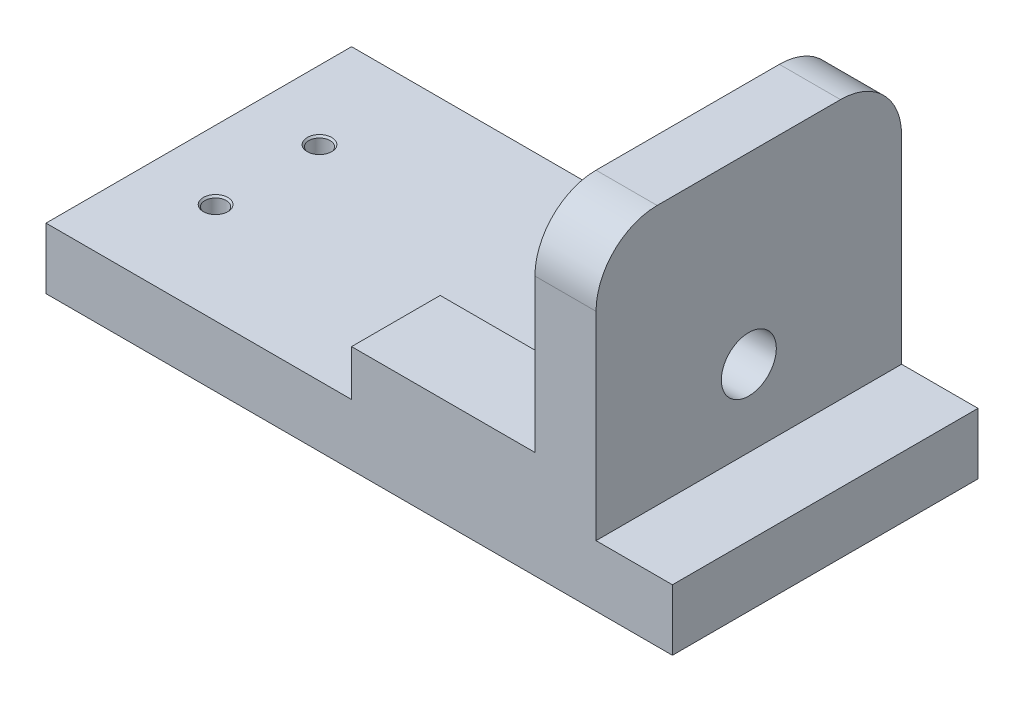
SolidWorks part; units mm, degrees
ref_plane "Piano frontale" through (0, 0, 0) normal (0, 0, 1) x (1, 0, 0)
ref_plane "Piano superiore" through (0, 0, 0) normal (0, 1, 0) x (1, 0, 0)
ref_plane "Piano destro" through (0, 0, 0) normal (1, 0, 0) x (0, 0, -1)
sketch "Schizzo1" plane through (0, 0, 0) normal (0, 1, 0) x (1, 0, 0)
  line L1 (-102.5, -50) -> (102.5, -50)
  line L2 (-102.5, -50) -> (-102.5, 50)
  line L3 (-102.5, 50) -> (102.5, 50)
  line L4 (102.5, -50) -> (102.5, 50)
  line L5 (-102.5, -50) -> (102.5, 50) construction
  line L6 (-102.5, 50) -> (102.5, -50) construction
  point P0 (0, 0)
  dimension "D1" = 100
  dimension "D2" = 205
extrude "Estrusione-Estrusione1" add sketch "Schizzo1" along normal blind 20
sketch "Schizzo2" plane through (0, 0, 0) normal (0, 1, 0) x (1, 0, 0)
  line L0 (77.5, 50) -> (77.5, -50)
  line L1 (102.5, 50) -> (-102.5, 50) construction
  line L2 (-102.5, -50) -> (102.5, -50) construction
  line L3 (77.5, -50) -> (-2.5, -50)
  line L4 (-2.5, -50) -> (-2.5, -21)
  line L5 (-2.5, -21) -> (57.5, -21)
  line L6 (57.5, -21) -> (57.5, 21)
  line L7 (57.5, 21) -> (-2.5, 21)
  line L8 (-2.5, 21) -> (-2.5, 50)
  line L9 (-2.5, 50) -> (77.5, 50)
  line L10 (102.5, -50) -> (102.5, 50) construction
  dimension "D1" = 20
  dimension "D2" = 80
  dimension "D3" = 25
  dimension "D4" = 29
extrude "Estrusione-Estrusione2" add sketch "Schizzo2" along normal blind 85 from surface at 20 starting at face at (0, 20, 0)
sketch "Schizzo4" plane through (0, 0, 0) normal (0, 0, 1) x (1, 0, 0)
  line L0 (-102.5, 20) -> (-2.5, 20) construction
  line L1 (-2.5, 105) -> (57.5, 105)
  line L2 (-2.5, 105) -> (-2.5, 35)
  line L3 (-2.5, 35) -> (57.5, 35)
  line L4 (57.5, 105) -> (57.5, 35)
  dimension "D1" = 20
  dimension "D2" = 15
extrude "Taglio-Estrusione1" cut sketch "Schizzo4" against normal through all both and the other way through all
sketch "Schizzo6" plane through (0, 0, 0) normal (1, 0, 0) x (0, 0, -1)
  line L0 (-50, 0) -> (50, 0) construction
  line L1 (-50, 105) -> (50, 105) construction
  line L2 (-50, 85) -> (-50, 105)
  line L3 (-50, 105) -> (-30, 105)
  line L4 (30, 105) -> (50, 105)
  line L5 (50, 105) -> (50, 85)
  line L6 (50, 105) -> (50, 20) construction
  circle A0 centre (0, 45) radius 9
  arc A1 (-30, 105) -> (-50, 85) centre (-30, 85) ccw
  arc A2 (30, 105) -> (50, 85) centre (30, 85) cw
  dimension "D2" = 18
  dimension "D4" = 20
  dimension "D5" = 20
  dimension "D1" = 45
extrude "Taglio-Estrusione2" cut sketch "Schizzo6" against normal up to next (2.5 mm away) from surface at 77.5 starting at face at (77.5, 62.5, 0)
sketch "Schizzo7" plane through (0, 0, 0) normal (0, 1, 0) x (1, 0, 0)
  line L0 (-102.5, 50) -> (-102.5, -50) construction
  line L1 (-102.5, -50) -> (-2.5, -50) construction
  point P0 (-80, -17)
  point P1 (-80, 17)
  dimension "D1" = 22.5
  dimension "D2" = 33
  dimension "D3" = 34
hole_wizard "Foro filettato M8x1.0-1" positions "Schizzo8" profile "Schizzo9" tap size "M8x1.0" standard "Ansi Metric" end condition through all
sketch "Schizzo8" plane through (0, 20, 0) normal (0, 1, 0) x (1, 0, 0)
  point P0 (-80, -17)
  point P3 (-80, 17)
sketch "Schizzo9" plane through (-80, 20, 17) normal (1, 0, 0) x (0, 0, 1)
  line L0 (0, 0) -> (0, 20)
  line L1 (0, 20) -> (3.5, 20)
  line L2 (3.5, 20) -> (3.5, 0.6039)
  line L3 (3.5, 0.6039) -> (4.025, 0)
  line L5 (4.025, 0) -> (0, 0)
  line L6 (-3.5, 0.6039) -> (-4.025, 0) construction
  line L11 (0, -6.35) -> (0, 107.95) construction
  dimension "Thru Tap Drill Dia." = 7
  dimension "Thru Tap Drill Depth" = 20
  dimension "Near C'Sink Dia." = 8.05
  dimension "Near C'Sink Angle" = 82
cosmetic thread "Filettatura del foro1" parameters "D2"=8
cosmetic thread "Filettatura del foro2" parameters "D2"=8
